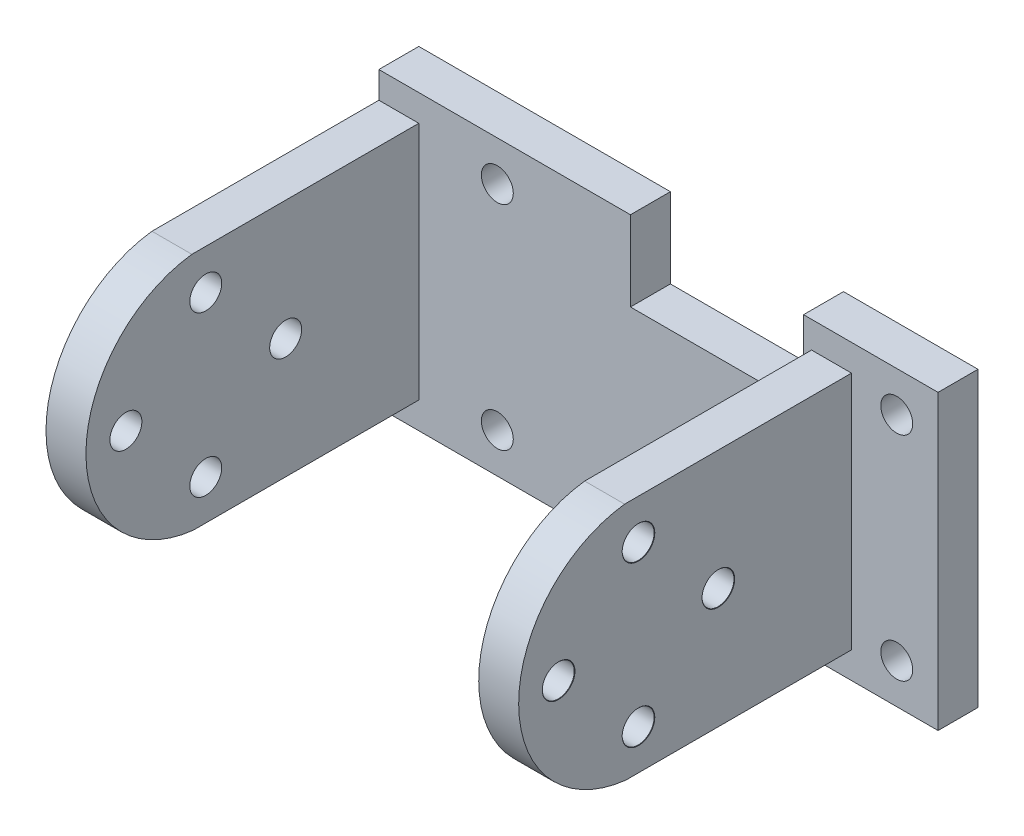
SolidWorks part; units mm, degrees
ref_plane "Front Plane" through (0, 0, 0) normal (0, 0, 1) x (1, 0, 0)
ref_plane "Top Plane" through (0, 0, 0) normal (0, 1, 0) x (1, 0, 0)
ref_plane "Right Plane" through (0, 0, 0) normal (1, 0, 0) x (0, 0, -1)
ref_plane "Plane1" through (0, 0, 163.527) normal (0, 0, 1) x (1, 0, 0)
sketch "Sketch1" plane through (0, 0, 163.527) normal (0, 0, 1) x (1, 0, 0)
  line L0 (36.2066, 229.3346) -> (-5.7934, 229.3346)
  line L1 (-5.7934, 229.3346) -> (-5.7934, 207.3346)
  line L2 (-5.7934, 207.3346) -> (36.2066, 207.3346)
  line L3 (36.2066, 207.3346) -> (36.2066, 229.3346)
extrude "Boss-Extrude1" add sketch "Sketch1" against normal blind 3
sketch "Sketch2" plane through (0, 0, 160.527) normal (0, 0, -1) x (-1, 0, 0)
  line L0 (-13.1033, 229.3346) -> (-26.1033, 229.3346)
  line L1 (-26.1033, 229.3346) -> (-26.1033, 223.3346)
  line L2 (-26.1033, 223.3346) -> (-13.1033, 223.3346)
  line L3 (-13.1033, 223.3346) -> (-13.1033, 229.3346)
extrude "Cut-Extrude1" cut sketch "Sketch2" against normal through all
sketch "Sketch3" plane through (0, 0, 160.527) normal (0, 0, -1) x (-1, 0, 0)
  line L0 (-26.1033, 207.3346) -> (-13.1033, 207.3346)
  line L1 (-13.1033, 207.3346) -> (-13.1033, 213.3346)
  line L2 (-13.1033, 213.3346) -> (-26.1033, 213.3346)
  line L3 (-26.1033, 213.3346) -> (-26.1033, 207.3346)
extrude "Cut-Extrude2" cut sketch "Sketch3" against normal through all
ref_plane "Plane2" through (-5.7934, 0, 0) normal (-1, 0, 0) x (0, -1, 0)
sketch "Sketch4" plane through (-5.7934, 0, 0) normal (-1, 0, 0) x (0, -1, 0)
  line L0 (-227.3346, 180.5701) -> (-227.3346, 163.527)
  line L1 (-227.3346, 163.527) -> (-209.3346, 163.527)
  line L2 (-209.3346, 163.527) -> (-209.3346, 180.4739)
  arc A0 (-209.3346, 180.4739) -> (-227.3346, 180.5701) centre (-218.3403, 179.465) ccw
extrude "Boss-Extrude2" add sketch "Sketch4" against normal blind 3
ref_plane "Plane3" through (29.7066, 0, 0) normal (1, 0, 0) x (0, 0, -1)
sketch "Sketch5" plane through (29.7066, 0, 0) normal (1, 0, 0) x (0, 0, -1)
  line L0 (-180.4739, 209.3346) -> (-163.527, 209.3346)
  line L1 (-163.527, 209.3346) -> (-163.527, 227.3346)
  line L2 (-163.527, 227.3346) -> (-180.5701, 227.3346)
  arc A0 (-180.5701, 227.3346) -> (-180.4739, 209.3346) centre (-179.465, 218.3403) ccw
extrude "Boss-Extrude3" add sketch "Sketch5" against normal blind 3
hole_wizard "M2 Clearance Hole1" positions "Sketch7" profile "Sketch6" hole size "M2" standard "ANSI Metric" end condition through all
sketch "Sketch7" plane through (29.7066, 0, 0) normal (1, 0, 0) x (0, 0, -1)
  point P0 (-179.5272, 224.3342)
  point P1 (-185.527, 218.3344)
  point P2 (-179.5272, 212.3346)
  point P3 (-173.5274, 218.3344)
sketch "Sketch6" plane through (29.7066, 224.3342, 179.5272) normal (0, 1, 0) x (0, 0, -1)
  line L0 (0, 0) -> (0, 35.5)
  line L1 (0, 35.5) -> (1.2, 35.5)
  line L2 (1.2, 35.5) -> (1.2, 0.025)
  line L3 (1.2, 0.025) -> (1.225, 0)
  line L5 (1.225, 0) -> (0, 0)
  line L6 (-1.2, 0.025) -> (-1.225, 0) construction
  line L11 (0, -6.35) -> (0, 107.95) construction
  dimension "Thru Hole Dia." = 2.4
  dimension "Thru Hole Depth" = 35.5
  dimension "Near C'Sink Dia." = 2.45
  dimension "Near C'Sink Angle" = 90
hole_wizard "M2 Clearance Hole2" positions "Sketch9" profile "Sketch8" hole size "M2" standard "ANSI Metric" end condition through all
sketch "Sketch9" plane through (0, 0, 163.527) normal (0, 0, 1) x (1, 0, 0)
  point P0 (3.1033, 226.327)
  point P1 (3.1033, 210.327)
  point P2 (33.1033, 210.327)
  point P3 (33.1033, 226.327)
sketch "Sketch8" plane through (3.1033, 226.327, 163.527) normal (1, 0, 0) x (0, -1, 0)
  line L0 (0, 0) -> (0, 3)
  line L1 (0, 3) -> (1.2, 3)
  line L2 (1.2, 3) -> (1.2, 0)
  line L5 (1.2, 0) -> (0, 0)
  line L11 (0, -6.35) -> (0, 107.95) construction
  dimension "Thru Hole Dia." = 2.4
  dimension "Thru Hole Depth" = 3
hole_wizard "Ø2.0 (2) Diameter Hole2" positions "Sketch11" profile "Sketch10" hole size "Ø2.0" standard "ANSI Metric"
sketch "Sketch11" plane through (-5.7934, 0, 0) normal (-1, 0, 0) x (0, 0, 1)
  point P0 (179.5272, 224.3342)
  point P1 (185.527, 218.3344)
  point P2 (179.5272, 212.3346)
  point P3 (173.5274, 218.3344)
sketch "Sketch10" plane through (-5.7934, 224.3342, 179.5272) normal (0, 1, 0) x (0, 0, 1)
  line L0 (0, 0) -> (0, 42)
  line L1 (0, 42) -> (1, 42)
  line L2 (1, 42) -> (1, 1.8)
  line L3 (1, 1.8) -> (2.8, 0)
  line L5 (2.8, 0) -> (0, 0)
  line L6 (-1, 1.8) -> (-2.8, 0) construction
  line L11 (0, -6.35) -> (0, 107.95) construction
  dimension "Thru Hole Dia." = 2
  dimension "Thru Hole Depth" = 42
  dimension "Near C'Sink Dia." = 5.6
  dimension "Near C'Sink Angle" = 90
